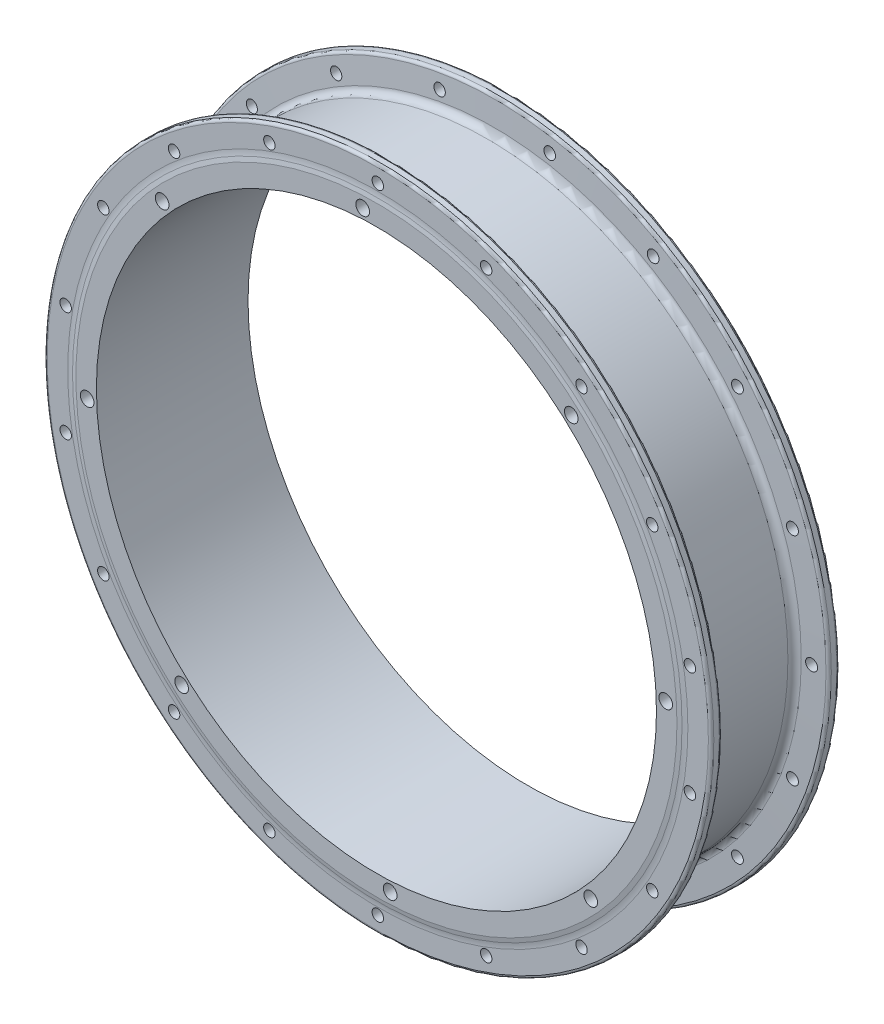
SolidWorks part; units mm, degrees
material "1060 Сплав"
ref_plane "Спереди" through (0, 0, 0) normal (0, 0, 1) x (1, 0, 0)
ref_plane "Сверху" through (0, 0, 0) normal (0, 1, 0) x (1, 0, 0)
ref_plane "Справа" through (0, 0, 0) normal (1, 0, 0) x (0, 0, -1)
sketch "Эскиз1" plane through (0, 0, 0) normal (0, 1, 0) x (1, 0, 0)
  line L0 (0, 0) -> (0, 150) construction
  line L1 (0, 0) -> (-122, 0) construction
  line L2 (0, 24) -> (-110, 24) construction
  line L3 (0, 0) -> (-121, 0) construction
  line L4 (-110, 24) -> (-110, 6.8893)
  line L5 (-122, 1) -> (-122, 3.0008)
  line L6 (-121.0452, 3.9997) -> (-112.3869, 4.3919)
  line L7 (18.0519, 23.5) -> (-59.7289, 23.5) construction
  line L8 (-121, 47) -> (-113, 47)
  line L9 (-121.0452, 43.0003) -> (-112.3869, 42.6081)
  line L10 (-122, 46) -> (-122, 43.9992)
  line L11 (0, 47) -> (-121, 47) construction
  line L12 (-110, 24) -> (-110, 40.1107)
  line L13 (-110, 50) -> (-110, 55)
  line L14 (-110, 55) -> (0, 55)
  line L15 (-121, 0) -> (-113.5, 0)
  line L16 (-111.5508, -0.1918) -> (-110, -0.5)
  line L17 (-110, -0.5) -> (0, -0.5)
  line L18 (0, 55) -> (0, -0.5)
  arc A0 (-110, 6.8893) -> (-112.3869, 4.3919) centre (-112.5, 6.8893) cw
  arc A1 (-122, 1) -> (-121, 0) centre (-121, 1) ccw
  arc A2 (-122, 3.0008) -> (-121.0452, 3.9997) centre (-121, 3.0008) cw
  arc A3 (-122, 43.9992) -> (-121.0452, 43.0003) centre (-121, 43.9992) ccw
  arc A4 (-122, 46) -> (-121, 47) centre (-121, 46) cw
  arc A5 (-110, 40.1107) -> (-112.3869, 42.6081) centre (-112.5, 40.1107) ccw
  arc A6 (-113.5, 0) -> (-111.5508, -0.1918) centre (-113.5, -10) cw
  arc A7 (-113, 47) -> (-110, 50) centre (-113, 50) ccw
  point P10 (-110, 4.5)
  point P29 (-110, 42.5)
  point P40 (-112.516, 0)
  point P43 (-110, 47)
  dimension "D5" = 2.5
  dimension "D6" = 1
  dimension "D11" = 10
  dimension "D13" = 3
  dimension "D1" = 122
  dimension "D2" = 24
  dimension "D3" = 110
  dimension "D4" = 19.5
  dimension "D7" = 23.5
  dimension "D8" = 55
  dimension "D9" = 4
  dimension "D10" = 1
  dimension "D12" = 8.5
revolve "Повернуть1" add sketch "Эскиз1" angle 360 about L0
sketch "Эскиз2" plane through (0, 0, 0.5) normal (0, 0, 1) x (1, 0, 0)
  circle A0 centre (0, 0) radius 116 construction
  circle A1 centre (0, 116) radius 2.1
  circle A2 centre (39.6743, 109.0043) radius 2.1
  circle A3 centre (74.5634, 88.8612) radius 2.1
  circle A4 centre (100.4589, 58) radius 2.1
  circle A5 centre (114.2377, 20.1432) radius 2.1
  circle A6 centre (114.2377, -20.1432) radius 2.1
  circle A7 centre (100.4589, -58) radius 2.1
  circle A8 centre (74.5634, -88.8612) radius 2.1
  circle A9 centre (39.6743, -109.0043) radius 2.1
  circle A10 centre (0, -116) radius 2.1
  circle A11 centre (-39.6743, -109.0043) radius 2.1
  circle A12 centre (-74.5634, -88.8612) radius 2.1
  circle A13 centre (-100.4589, -58) radius 2.1
  circle A14 centre (-114.2377, -20.1432) radius 2.1
  circle A15 centre (-114.2377, 20.1432) radius 2.1
  circle A16 centre (-100.4589, 58) radius 2.1
  circle A17 centre (-74.5634, 88.8612) radius 2.1
  circle A18 centre (-39.6743, 109.0043) radius 2.1
  point P41 (0, 0)
  dimension "D1" = 232
  dimension "D2" = 4.2
  dimension "D3" = 18
extrude "Вырез-Вытянуть1" cut sketch "Эскиз2" against normal blind 10
sketch "Эскиз3" plane through (0, 0, -55) normal (0, 0, -1) x (-1, 0, 0)
  circle A0 centre (0, 0) radius 116 construction
  circle A1 centre (116, 0) radius 2.1
  circle A2 centre (109.0043, -39.6743) radius 2.1
  circle A3 centre (88.8612, -74.5634) radius 2.1
  circle A4 centre (58, -100.4589) radius 2.1
  circle A5 centre (20.1432, -114.2377) radius 2.1
  circle A6 centre (-20.1432, -114.2377) radius 2.1
  circle A7 centre (-58, -100.4589) radius 2.1
  circle A8 centre (-88.8612, -74.5634) radius 2.1
  circle A9 centre (-109.0043, -39.6743) radius 2.1
  circle A10 centre (-116, 0) radius 2.1
  circle A11 centre (-109.0043, 39.6743) radius 2.1
  circle A12 centre (-88.8612, 74.5634) radius 2.1
  circle A13 centre (-58, 100.4589) radius 2.1
  circle A14 centre (-20.1432, 114.2377) radius 2.1
  circle A15 centre (20.1432, 114.2377) radius 2.1
  circle A16 centre (58, 100.4589) radius 2.1
  circle A17 centre (88.8612, 74.5634) radius 2.1
  circle A18 centre (109.0043, 39.6743) radius 2.1
  point P42 (0, 0)
  dimension "D1" = 232
  dimension "D2" = 4.2
  dimension "D3" = 18
extrude "Вырез-Вытянуть2" cut sketch "Эскиз3" against normal blind 20
sketch "Эскиз4" plane through (0, 0, 0.5) normal (0, 0, 1) x (1, 0, 0)
  circle A0 centre (0, 0) radius 106 construction
  circle A1 centre (-5.0316, 105.8805) radius 2.5
  circle A2 centre (71.311, 78.4267) radius 2.5
  circle A3 centre (0, 0) radius 106 construction
  circle A4 centre (105.8805, 5.0316) radius 2.5
  circle A5 centre (0, 0) radius 106 construction
  circle A6 centre (78.4267, -71.311) radius 2.5
  circle A7 centre (0, 0) radius 106 construction
  circle A8 centre (5.0316, -105.8805) radius 2.5
  circle A9 centre (0, 0) radius 106 construction
  circle A10 centre (-71.311, -78.4267) radius 2.5
  circle A11 centre (0, 0) radius 106 construction
  circle A12 centre (-105.8805, -5.0316) radius 2.5
  circle A13 centre (0, 0) radius 106 construction
  circle A14 centre (-78.4267, 71.311) radius 2.5
  circle A15 centre (0, 0) radius 106 construction
  point P17 (0, 0)
  dimension "D1" = 212
  dimension "D2" = 5
  dimension "D4" = 81.1289
  dimension "D3" = 8
extrude "Вырез-Вытянуть4" cut sketch "Эскиз4" against normal blind 25
sketch "Эскиз5" plane through (0, 0, -55) normal (0, 0, -1) x (-1, 0, 0)
  circle A0 centre (0, 0) radius 106 construction
  circle A1 centre (-16.1193, 104.7672) radius 2.5
  circle A2 centre (62.6836, 85.4797) radius 2.5
  circle A3 centre (104.7672, 16.1193) radius 2.5
  circle A4 centre (85.4797, -62.6836) radius 2.5
  circle A5 centre (16.1193, -104.7672) radius 2.5
  circle A6 centre (-62.6836, -85.4797) radius 2.5
  circle A7 centre (-104.7672, -16.1193) radius 2.5
  circle A8 centre (-85.4797, 62.6836) radius 2.5
  point P22 (0, 0)
  dimension "D1" = 212
  dimension "D2" = 5
  dimension "D3" = 8
extrude "Вырез-Вытянуть5" cut sketch "Эскиз5" against normal blind 25
sketch "Эскиз6" plane through (0, 0, -55) normal (0, 0, -1) x (-1, 0, 0)
  circle A0 centre (0, 0) radius 102.5
  dimension "D1" = 205
extrude "Вырез-Вытянуть6" cut sketch "Эскиз6" against normal through all
